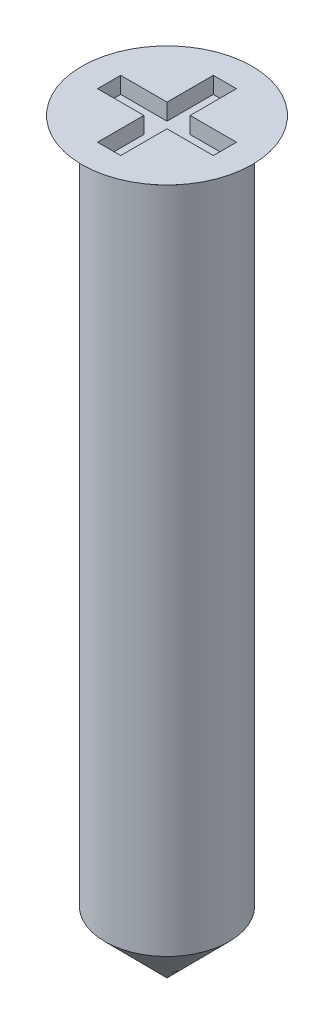
SolidWorks part; units mm, degrees
ref_plane "Front Plane" through (0, 0, 0) normal (0, 0, 1) x (1, 0, 0)
ref_plane "Top Plane" through (0, 0, 0) normal (0, 1, 0) x (1, 0, 0)
ref_plane "Right Plane" through (0, 0, 0) normal (1, 0, 0) x (0, 0, -1)
sketch "Sketch1" plane through (0, 0, 0) normal (0, 0, 1) x (1, 0, 0)
  line L0 (-7.3786, 0) -> (4.9893, 0) construction
  line L1 (0, 12.9125) -> (0, -10.8395) construction
  line L2 (0, 0) -> (0.75, 0.7554)
  line L3 (0.75, 0.7554) -> (0.75, 8.83)
  line L4 (0.75, 8.83) -> (1.03, 9.03)
  line L5 (1.03, 9.03) -> (0, 9.03)
  line L6 (0, 9.03) -> (0, 0)
  dimension "D1" = 9.03
  dimension "D2" = 0.2
  dimension "D3" = 0.75
  dimension "D4" = 0.28
revolve "Revolve1" add sketch "Sketch1" angle 360 about L1
sketch "Sketch2" plane through (0, 9.03, 0) normal (0, 1, 0) x (1, 0, 0)
  line L0 (-0.14, 0.14) -> (-0.14, 0.7)
  line L1 (0.14, -0.7) -> (-0.14, -0.7)
  line L2 (0.14, -0.7) -> (0.14, -0.14)
  line L3 (0.14, 0.7) -> (-0.14, 0.7)
  line L4 (-0.14, -0.7) -> (-0.14, -0.14)
  line L5 (0.14, -0.7) -> (-0.14, 0.7) construction
  line L6 (0.14, 0.7) -> (-0.14, -0.7) construction
  line L7 (0.7, -0.14) -> (0.14, -0.14)
  line L8 (0.7, -0.14) -> (0.7, 0.14)
  line L9 (0.7, 0.14) -> (0.14, 0.14)
  line L10 (-0.7, -0.14) -> (-0.7, 0.14)
  line L11 (0.7, -0.14) -> (-0.7, 0.14) construction
  line L12 (0.7, 0.14) -> (-0.7, -0.14) construction
  line L13 (0.14, 0.14) -> (0.14, 0.7)
  line L14 (-0.14, 0.14) -> (-0.7, 0.14)
  line L15 (-0.14, -0.14) -> (-0.7, -0.14)
  point P0 (0, 0)
  point P6 (0, 0)
  dimension "D1" = 0.28
  dimension "D2" = 0.28
  dimension "D3" = 1.4
  dimension "D4" = 1.4
extrude "Cut-Extrude1" cut sketch "Sketch2" against normal blind 0.2
